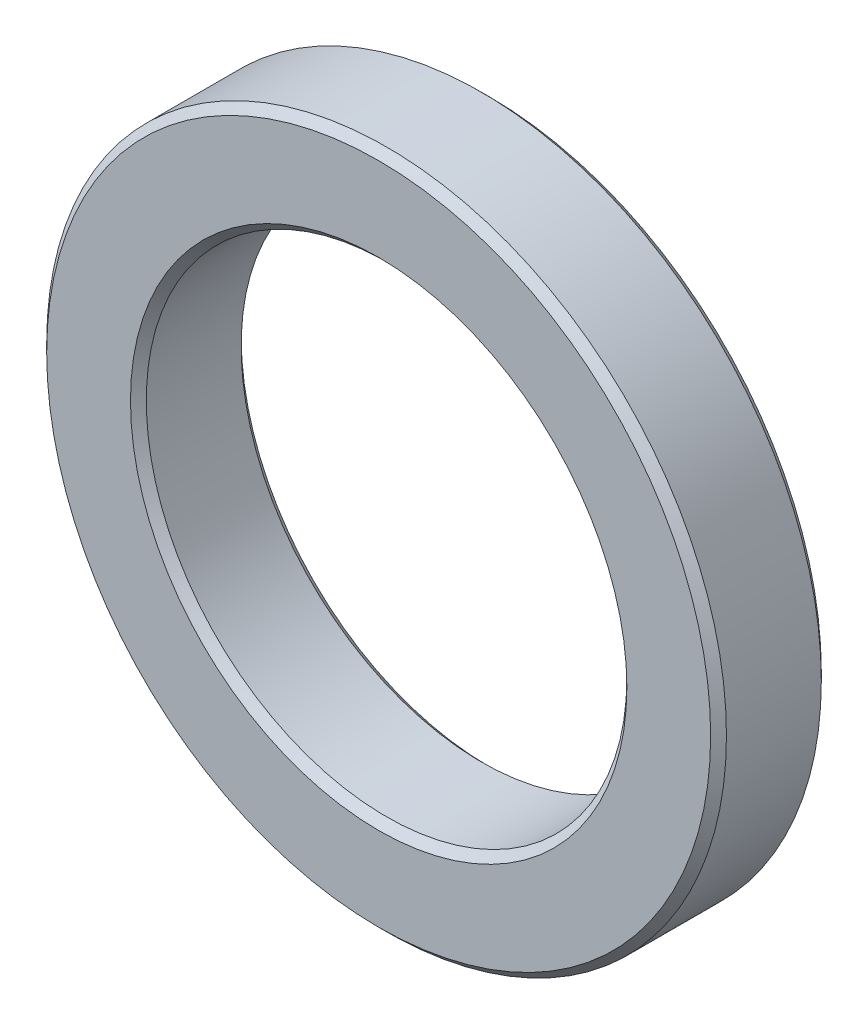
SolidWorks part; units mm, degrees
material "镀铬不锈钢"
ref_plane "前视基准面" through (0, 0, 0) normal (0, 0, 1) x (1, 0, 0)
ref_plane "上视基准面" through (0, 0, 0) normal (0, 1, 0) x (1, 0, 0)
ref_plane "右视基准面" through (0, 0, 0) normal (1, 0, 0) x (0, 0, -1)
sketch "草图1" plane through (0, 0, 0) normal (0, 0, 1) x (1, 0, 0)
  circle A0 centre (0, 0) radius 21.5
  circle A1 centre (0, 0) radius 15.2
  dimension "D1" = 30.4
  dimension "D2" = 43
extrude "凸台-拉伸1" add sketch "草图1" along normal mid plane 7
chamfer "倒角1" distance 0.5 angle 45 4 edges at (15.2, 0, -3.5) (15.2, 0, 3.5) (21.5, 0, -3.5) (21.5, 0, 3.5)
equation "\"24。6\"=4.7186"
